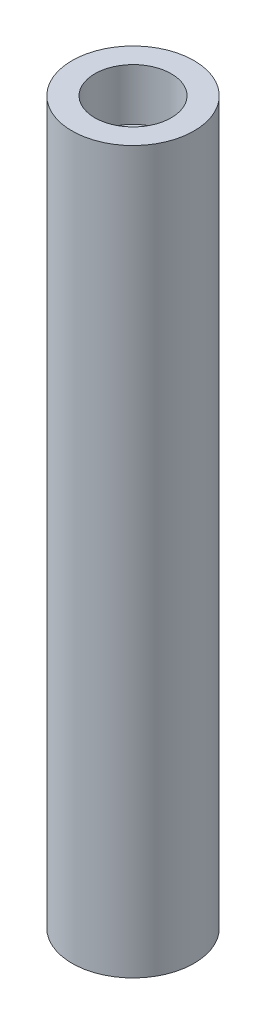
SolidWorks part; units mm, degrees
ref_plane "Front Plane" through (0, 0, 0) normal (0, 0, 1) x (1, 0, 0)
ref_plane "Top Plane" through (0, 0, 0) normal (0, 1, 0) x (1, 0, 0)
ref_plane "Right Plane" through (0, 0, 0) normal (1, 0, 0) x (0, 0, -1)
sketch "Sketch1" plane through (0, 0, 0) normal (0, 1, 0) x (1, 0, 0)
  circle A0 centre (0, 0) radius 4.95
  dimension "D1" = 9.9
extrude "Boss-Extrude1" add sketch "Sketch1" along normal blind 58.5
sketch "Sketch2" plane through (0, 58.5, 0) normal (0, 1, 0) x (1, 0, 0)
  circle A0 centre (0, 0) radius 3.1
  dimension "D1" = 6.2
extrude "Cut-Extrude1" cut sketch "Sketch2" against normal blind 4.2
